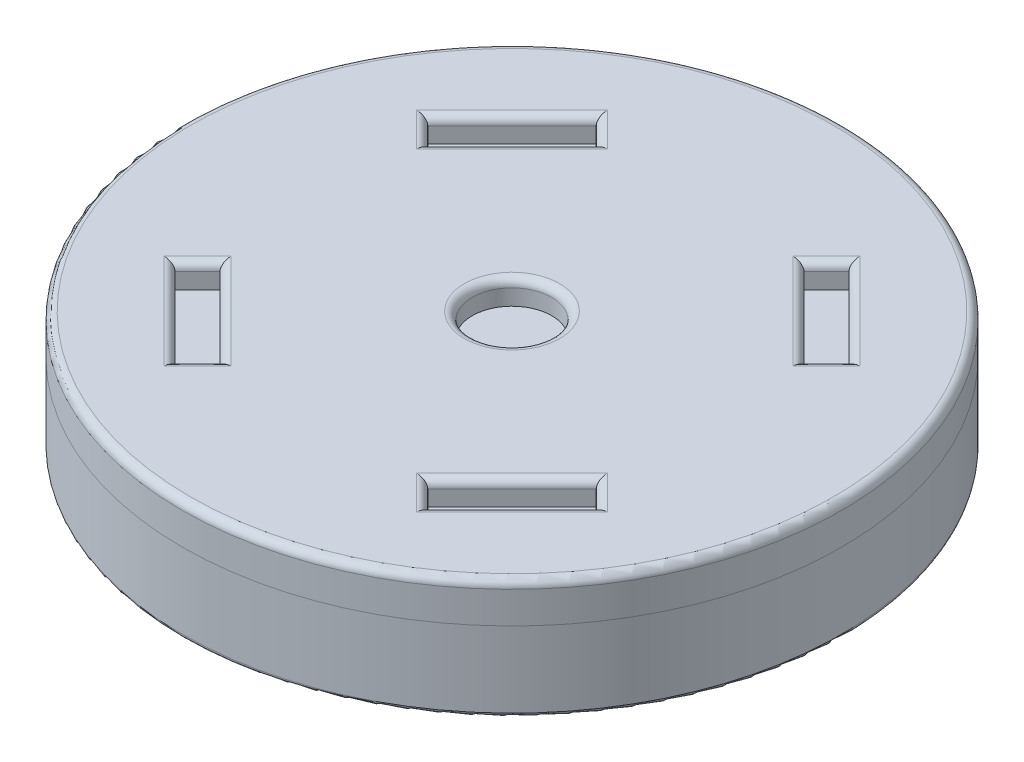
SolidWorks part; units mm, degrees
ref_plane "Front Plane" through (0, 0, 0) normal (0, 0, 1) x (1, 0, 0)
ref_plane "Top Plane" through (0, 0, 0) normal (0, 1, 0) x (1, 0, 0)
ref_plane "Right Plane" through (0, 0, 0) normal (1, 0, 0) x (0, 0, -1)
sketch "Sketch1" plane through (0, 0, 0) normal (0, 1, 0) x (1, 0, 0)
  line L1 (29, 0) -> (29, 3)
  line L2 (29, 0) -> (29, -3)
  line L5 (29, 3) -> (24.33, 5.7489)
  line L6 (29, -3) -> (24.33, -5.7489)
  line L9 (25.2248, -14.6187) -> (23.0625, -9.6498)
  line L10 (23.4615, -17.0458) -> (25.2248, -14.6187)
  line L11 (23.4615, -17.0458) -> (21.6981, -19.4728)
  line L12 (21.6981, -19.4728) -> (16.3043, -18.9518)
  line L15 (11.8147, -26.6536) -> (12.986, -21.3627)
  line L16 (8.9615, -27.5806) -> (11.8147, -26.6536)
  line L17 (8.9615, -27.5806) -> (6.1083, -28.5077)
  line L18 (6.1083, -28.5077) -> (2.0508, -24.9157)
  line L21 (-6.1083, -28.5077) -> (-2.0508, -24.9157)
  line L22 (-8.9615, -27.5806) -> (-6.1083, -28.5077)
  line L23 (-8.9615, -27.5806) -> (-11.8147, -26.6536)
  line L24 (-11.8147, -26.6536) -> (-12.986, -21.3627)
  line L27 (-21.6981, -19.4728) -> (-16.3043, -18.9518)
  line L28 (-23.4615, -17.0458) -> (-21.6981, -19.4728)
  line L29 (-23.4615, -17.0458) -> (-25.2248, -14.6187)
  line L30 (-25.2248, -14.6187) -> (-23.0625, -9.6498)
  line L33 (-29, -3) -> (-24.33, -5.7489)
  line L34 (-29, 0) -> (-29, -3)
  line L35 (-29, 0) -> (-29, 3)
  line L36 (-29, 3) -> (-24.33, 5.7489)
  line L39 (-25.2248, 14.6187) -> (-23.0625, 9.6498)
  line L40 (-23.4615, 17.0458) -> (-25.2248, 14.6187)
  line L41 (-23.4615, 17.0458) -> (-21.6981, 19.4728)
  line L42 (-21.6981, 19.4728) -> (-16.3043, 18.9518)
  line L45 (-11.8147, 26.6536) -> (-12.986, 21.3627)
  line L46 (-8.9615, 27.5806) -> (-11.8147, 26.6536)
  line L47 (-8.9615, 27.5806) -> (-6.1083, 28.5077)
  line L48 (-6.1083, 28.5077) -> (-2.0508, 24.9157)
  line L51 (6.1083, 28.5077) -> (2.0508, 24.9157)
  line L52 (8.9615, 27.5806) -> (6.1083, 28.5077)
  line L53 (8.9615, 27.5806) -> (11.8147, 26.6536)
  line L54 (11.8147, 26.6536) -> (12.986, 21.3627)
  line L57 (21.6981, 19.4728) -> (16.3043, 18.9518)
  line L58 (23.4615, 17.0458) -> (21.6981, 19.4728)
  line L59 (23.4615, 17.0458) -> (25.2248, 14.6187)
  line L60 (25.2248, 14.6187) -> (23.0625, 9.6498)
  arc A0 (24.33, 5.7489) -> (23.0625, 9.6498) centre (0, 0) ccw
  arc A1 (16.3043, 18.9518) -> (12.986, 21.3627) centre (0, 0) ccw
  arc A2 (2.0508, 24.9157) -> (-2.0508, 24.9157) centre (0, 0) ccw
  arc A3 (-12.986, 21.3627) -> (-16.3043, 18.9518) centre (0, 0) ccw
  arc A4 (-23.0625, 9.6498) -> (-24.33, 5.7489) centre (0, 0) ccw
  arc A5 (-24.33, -5.7489) -> (-23.0625, -9.6498) centre (0, 0) ccw
  arc A6 (-16.3043, -18.9518) -> (-12.986, -21.3627) centre (0, 0) ccw
  arc A7 (-2.0508, -24.9157) -> (2.0508, -24.9157) centre (0, 0) ccw
  arc A8 (12.986, -21.3627) -> (16.3043, -18.9518) centre (0, 0) ccw
  arc A9 (23.0625, -9.6498) -> (24.33, -5.7489) centre (0, 0) ccw
  circle A10 centre (0, 0) radius 41.5
  point P66 (0, 0)
  dimension "D1" = 10
extrude "Boss-Extrude1" add sketch "Sketch1" along normal blind 10
sketch "Sketch2" plane through (0, 10, 0) normal (0, 1, 0) x (1, 0, 0)
  circle A0 centre (0, 0) radius 41.5
extrude "Boss-Extrude2" add sketch "Sketch2" along normal blind 5
sketch "Sketch3" plane through (0, 15, 0) normal (0, 1, 0) x (1, 0, 0)
  line L7 (-21.2132, 21.2132) -> (-26.5165, 15.9099)
  line L8 (-21.2132, 21.2132) -> (-15.9099, 26.5165)
  line L9 (-26.5165, 15.9099) -> (-23.6881, 13.0815)
  line L10 (-15.9099, 26.5165) -> (-13.0815, 23.6881)
  line L11 (-13.0815, 23.6881) -> (-23.6881, 13.0815)
  line L12 (23.6881, 13.0815) -> (13.0815, 23.6881)
  line L13 (26.5165, 15.9099) -> (23.6881, 13.0815)
  line L14 (21.2132, 21.2132) -> (26.5165, 15.9099)
  line L15 (21.2132, 21.2132) -> (15.9099, 26.5165)
  line L16 (15.9099, 26.5165) -> (13.0815, 23.6881)
  line L17 (13.0815, -23.6881) -> (23.6881, -13.0815)
  line L18 (15.9099, -26.5165) -> (13.0815, -23.6881)
  line L19 (21.2132, -21.2132) -> (15.9099, -26.5165)
  line L20 (21.2132, -21.2132) -> (26.5165, -15.9099)
  line L21 (26.5165, -15.9099) -> (23.6881, -13.0815)
  line L22 (-23.6881, -13.0815) -> (-13.0815, -23.6881)
  line L23 (-26.5165, -15.9099) -> (-23.6881, -13.0815)
  line L24 (-21.2132, -21.2132) -> (-26.5165, -15.9099)
  line L25 (-21.2132, -21.2132) -> (-15.9099, -26.5165)
  line L26 (-15.9099, -26.5165) -> (-13.0815, -23.6881)
  circle A0 centre (0, 0) radius 5
  point P0 (0, 0)
  point P30 (0, 0)
  dimension "D1" = 4
extrude "Cut-Extrude1" cut sketch "Sketch3" against normal blind 3
fillet "Fillet1" radius 1 18 edges at (0, 15, 41.5) (-14.4957, 15, 25.1023) (-21.2132, 15, 21.2132) (-25.1023, 15, 14.4957) (-18.3848, 15, 18.3848) (21.2132, 15, 21.2132) (14.4957, 15, 25.1023) (18.3848, 15, 18.3848) (25.1023, 15, 14.4957) (25.1023, 15, -14.4957) (18.3848, 15, -18.3848) (14.4957, 15, -25.1023) (21.2132, 15, -21.2132) (0, 15, 5) (-25.1023, 15, -14.4957) (-18.3848, 15, -18.3848) (-14.4957, 15, -25.1023) (-21.2132, 15, -21.2132)
fillet "Fillet2" radius 0.5 41 edges at (26.665, 0, -4.3745) (29, 0, 0) (26.665, 0, 4.3745) (23.7764, 0, 7.7254) (24.1437, 0, 12.1343) (23.4615, 0, 17.0458) (19.0012, 0, 19.2123) (14.6946, 0, 20.2254) (12.4003, 0, 24.0081) (8.9615, 0, 27.5806) (4.0796, 0, 26.7117) (0, 0, 25) (-4.0796, 0, 26.7117) (-8.9615, 0, 27.5806) (-12.4003, 0, 24.0081) (-14.6946, 0, 20.2254) (-19.0012, 0, 19.2123) (-23.4615, 0, 17.0458) (-24.1437, 0, 12.1343) (-23.7764, 0, 7.7254) (-26.665, 0, 4.3745) (-29, 0, 0) (-26.665, 0, -4.3745) (-23.7764, 0, -7.7254) (-24.1437, 0, -12.1343) (-23.4615, 0, -17.0458) (-19.0012, 0, -19.2123) (-14.6946, 0, -20.2254) (-12.4003, 0, -24.0081) (-8.9615, 0, -27.5806) (-4.0796, 0, -26.7117) (0, 0, -25) (4.0796, 0, -26.7117) (8.9615, 0, -27.5806) (12.4003, 0, -24.0081) (14.6946, 0, -20.2254) (19.0012, 0, -19.2123) (23.4615, 0, -17.0458) (24.1437, 0, -12.1343) (23.7764, 0, -7.7254) (0, 0, 41.5)
